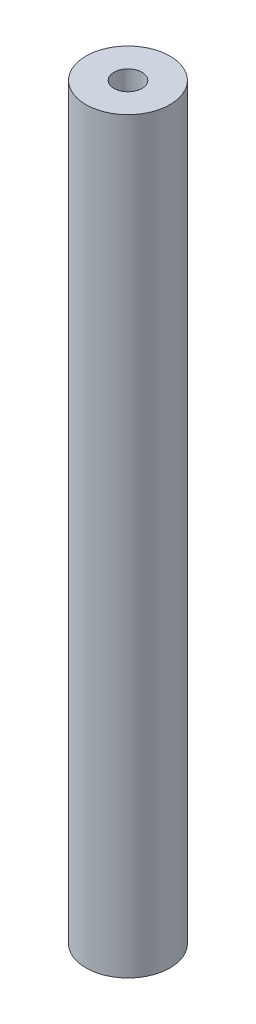
SolidWorks part; units mm, degrees
ref_plane "前视基准面" through (0, 0, 0) normal (0, 0, 1) x (1, 0, 0)
ref_plane "上视基准面" through (0, 0, 0) normal (0, 1, 0) x (1, 0, 0)
ref_plane "右视基准面" through (0, 0, 0) normal (1, 0, 0) x (0, 0, -1)
sketch "草图1" plane through (0, 0, 0) normal (0, 1, 0) x (1, 0, 0)
  circle A0 centre (0, 0) radius 4.5
  dimension "D1" = 9
extrude "凸台-拉伸1" add sketch "草图1" along normal blind 80
sketch "草图2" plane through (0, 80, 0) normal (0, 1, 0) x (1, 0, 0)
  circle A0 centre (0, 0) radius 1.5
  dimension "D1" = 3
extrude "切除-拉伸1" cut sketch "草图2" against normal blind 10
sketch "草图3" plane through (0, 0, 0) normal (0, -1, 0) x (1, 0, 0)
  circle A0 centre (0, 0) radius 1.5
  dimension "D1" = 3
extrude "切除-拉伸2" cut sketch "草图3" against normal blind 10
